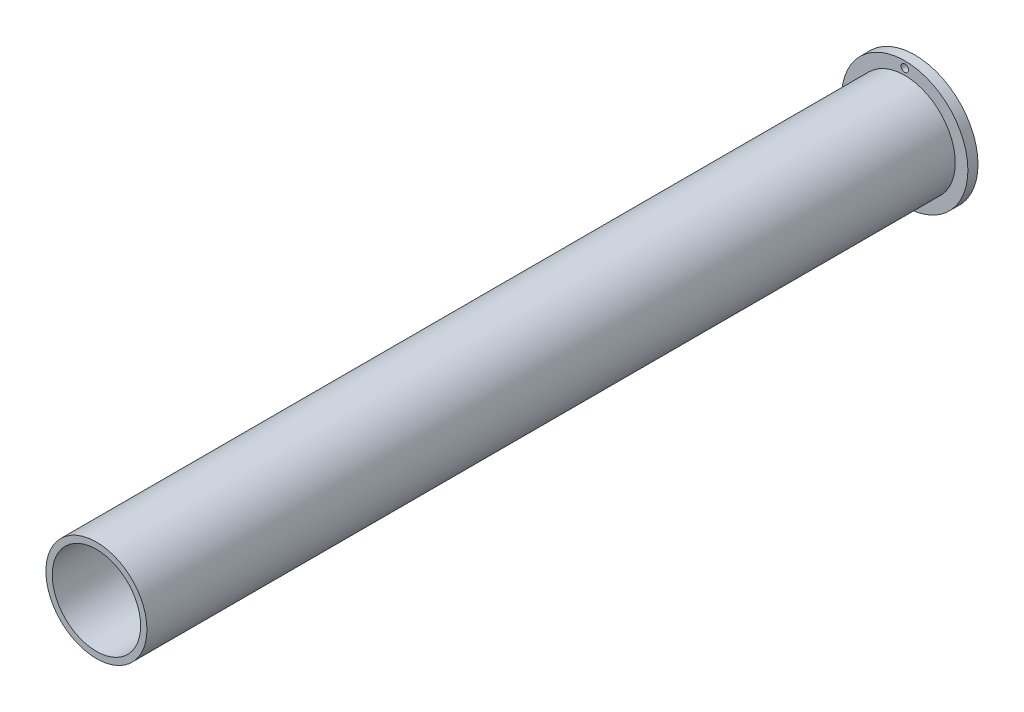
SolidWorks part; units mm, degrees
ref_plane "Front Plane" through (0, 0, 0) normal (0, 0, 1) x (1, 0, 0)
ref_plane "Top Plane" through (0, 0, 0) normal (0, 1, 0) x (1, 0, 0)
ref_plane "Right Plane" through (0, 0, 0) normal (1, 0, 0) x (0, 0, -1)
sketch "Sketch1" plane through (0, 0, 0) normal (0, 0, 1) x (1, 0, 0)
  circle A0 centre (0, 0) radius 15.875
  dimension "D1" = 31.75
extrude "Boss-Extrude1" add sketch "Sketch1" along normal blind 2.54
sketch "Sketch2" plane through (0, 0, 2.54) normal (0, 0, 1) x (1, 0, 0)
  circle A0 centre (0, 0) radius 12.7
  circle A1 centre (0, 0) radius 11.1125
  dimension "D1" = 25.4
  dimension "D2" = 22.225
extrude "Boss-Extrude2" add sketch "Sketch2" along normal blind 203.2
sketch "Sketch3" plane through (0, 0, 2.54) normal (0, 0, 1) x (1, 0, 0)
  line L0 (0, 0) -> (0, 6.3672) construction
  line L1 (0, 0) -> (-8.128, 0) construction
  circle A0 centre (-8.128, 0) radius 1.778
  circle A1 centre (8.128, 0) radius 1.778
  dimension "D2" = 3.556
  dimension "D1" = 8.128
extrude "Cut-Extrude1" cut sketch "Sketch3" against normal up to surface (2.54 mm away) up to face at (15.875, 0, 0)
sketch "Sketch4" plane through (0, 0, 2.54) normal (0, 0, 1) x (1, 0, 0)
  line L0 (0, 0) -> (15.875, 0) construction
  line L1 (0, 12.7) -> (0, 15.875) construction
  circle A0 centre (0, 14.2875) radius 0.9271
  circle A1 centre (0, 0) radius 15.875 construction
  circle A2 centre (0, 0) radius 12.7 construction
  circle A3 centre (0, -14.2875) radius 0.9271
  dimension "D1" = 1.8542
extrude "Cut-Extrude2" cut sketch "Sketch4" against normal up to surface (2.54 mm away) up to face at (-6.35, 0, 0)
